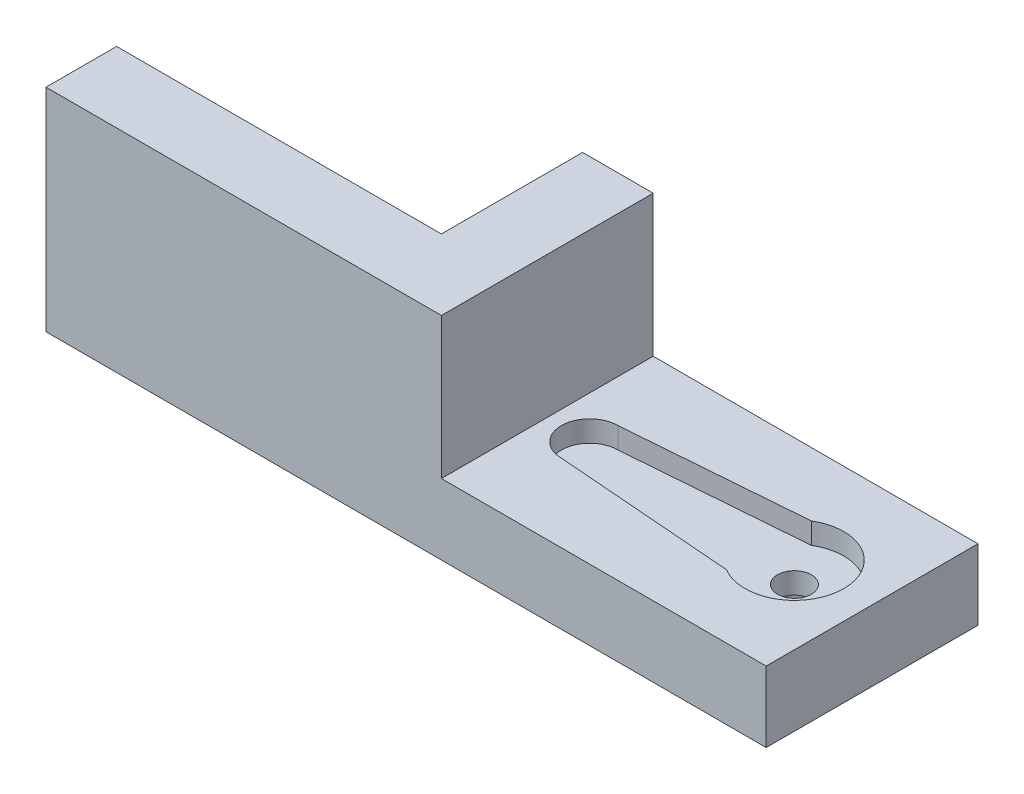
SolidWorks part; units mm, degrees
ref_plane "Front" through (0, 0, 0) normal (0, 0, 1) x (1, 0, 0)
ref_plane "Top" through (0, 0, 0) normal (0, 1, 0) x (1, 0, 0)
ref_plane "Right" through (0, 0, 0) normal (1, 0, 0) x (0, 0, -1)
sketch "草图1" plane through (0, 0, 0) normal (0, 1, 0) x (1, 0, 0)
  line L1 (-14, 7.5) -> (14, 7.5)
  line L2 (-14, 7.5) -> (-14, -7.5)
  line L3 (-14, -7.5) -> (14, -7.5)
  line L4 (14, 7.5) -> (14, -7.5)
  line L5 (-14, 7.5) -> (14, -7.5) construction
  line L6 (-14, -7.5) -> (14, 7.5) construction
  point P0 (0, 0)
  dimension "D1" = 28
  dimension "D2" = 15
extrude "凸台-拉伸1" add sketch "草图1" along normal blind 5
sketch "草图2" plane through (0, 5, 0) normal (0, 1, 0) x (1, 0, 0)
  line L0 (-14, -7.5) -> (14, -7.5) construction
  line L1 (-14, 7.5) -> (-9, 7.5)
  line L2 (-14, 7.5) -> (-14, -7.5)
  line L3 (-14, -7.5) -> (-9, -7.5)
  line L4 (-9, 7.5) -> (-9, -7.5)
  dimension "D1" = 5
extrude "凸台-拉伸2" add sketch "草图2" along normal blind 10
sketch "草图3" plane through (-14, 0, 0) normal (-1, 0, 0) x (0, 0, 1)
  line L0 (-7.5, 0) -> (7.5, 0) construction
  line L1 (7.5, 15) -> (2.5, 15)
  line L2 (7.5, 15) -> (7.5, 0)
  line L3 (7.5, 0) -> (2.5, 0)
  line L4 (2.5, 15) -> (2.5, 0)
  dimension "D1" = 5
extrude "凸台-拉伸3" add sketch "草图3" along normal blind 23
sketch "草图4" plane through (0, 5, 0) normal (0, 1, 0) x (1, 0, 0)
  line L1 (14, -7.5) -> (14, 7.5) construction
  line L2 (14, 7.5) -> (-9, 7.5) construction
  line L3 (-6, 2) -> (6.6972, 3)
  line L4 (-6, -2) -> (6.6972, -3)
  arc A0 (6.6972, -3) -> (6.6972, 3) centre (8.5, 0) ccw
  arc A1 (-6, 2) -> (-6, -2) centre (-6, 0) ccw
  dimension "D1" = 7
  dimension "D2" = 4
  dimension "D3" = 14.5
  dimension "D4" = 7.5
  dimension "D5" = 5.5
  dimension "D6" = 6
  dimension "D7" = 7.5
  dimension "D8" = 12.6972
extrude "切除-拉伸1" cut sketch "草图4" against normal blind 1.5
sketch "草图5" plane through (0, 0, 0) normal (0, -1, 0) x (1, 0, 0)
  point P0 (8.5, 0)
hole_wizard "M2 凹头盖螺钉的柱形沉头孔1" positions "3D草图1" profile "草图6" counterbore size "M2" standard "ANSI Metric" end condition up to next
sketch3d "3D草图1"
  point P0 (8.5, 0, 0)
sketch "草图6" plane through (8.5, 0, 0) normal (1, 0, 0) x (0, 0, -1)
  line L0 (0, 0) -> (0, 3.5)
  line L1 (0, 3.5) -> (1.2, 3.5)
  line L3 (1.2, 3.5) -> (1.2, 2)
  line L4 (1.2, 2) -> (2.2, 2)
  line L5 (2.2, 2) -> (2.2, 0)
  line L7 (2.2, 0) -> (0, 0)
  line L11 (0, -6.35) -> (0, 107.95) construction
  dimension "通孔孔直径" = 2.4
  dimension "通孔孔深度" = 3.5
  dimension "柱形沉头孔直径" = 4.4
  dimension "柱形沉头孔深度" = 2
sketch "草图7" plane through (0, 0, 2.5) normal (0, 0, -1) x (-1, 0, 0)
  line L0 (37, 15) -> (14, 15) construction
  line L1 (37, 15) -> (37, 0) construction
  line L3 (17, 9.5) -> (29.6972, 10.5)
  line L4 (17, 5.5) -> (29.6972, 4.5)
  arc A0 (29.6972, 4.5) -> (29.6972, 10.5) centre (31.5, 7.5) ccw
  arc A1 (17, 9.5) -> (17, 5.5) centre (17, 7.5) ccw
  dimension "D1" = 4
  dimension "D2" = 7
  dimension "D3" = 7.5
  dimension "D4" = 7.5
  dimension "D5" = 14.5
  dimension "D6" = 5.5
  dimension "D7" = 6
extrude "切除-拉伸2" cut sketch "草图7" against normal blind 1.5
